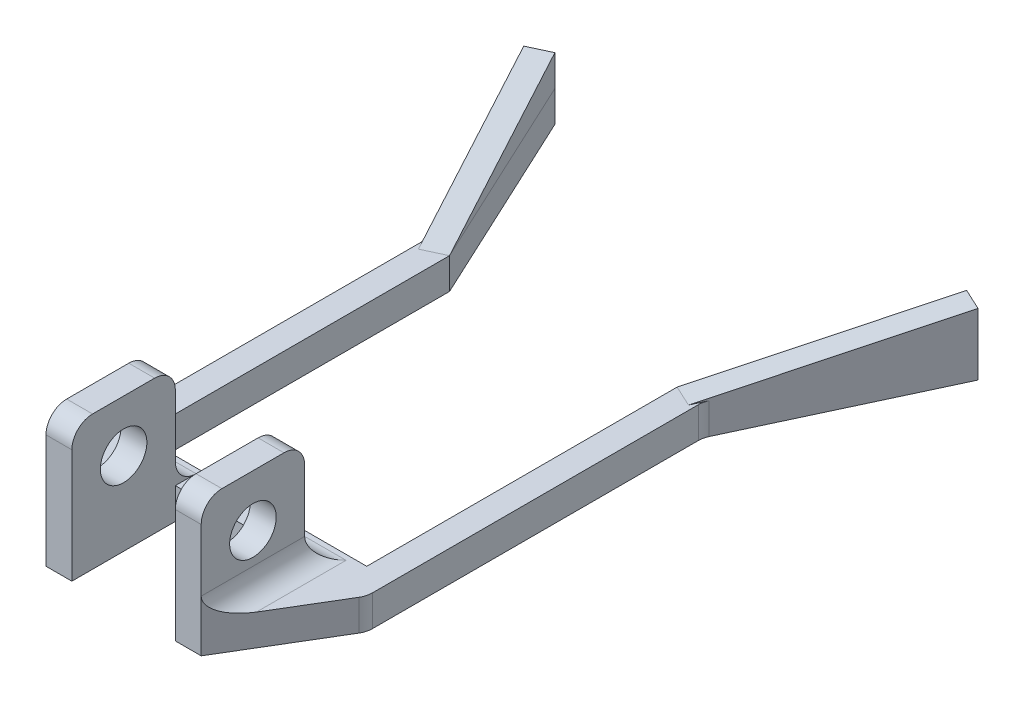
SolidWorks part; units mm, degrees
material "PET"
ref_plane "Front Plane" through (0, 0, 0) normal (0, 0, 1) x (1, 0, 0)
ref_plane "Top Plane" through (0, 0, 0) normal (0, 1, 0) x (1, 0, 0)
ref_plane "Right Plane" through (0, 0, 0) normal (1, 0, 0) x (0, 0, -1)
sketch "Sketch1" plane through (0, 0, 0) normal (0, 1, 0) x (1, 0, 0)
  line L0 (0, -55) -> (0, 55) construction
  line L12 (11, 0) -> (11, 30)
  line L15 (-11, 0) -> (-11, 30)
  line L16 (-11, 0) -> (11, 0)
  line L17 (-13.5, 30) -> (-13.5, -2.5)
  line L18 (13.5, -2.5) -> (13.5, 30)
  line L19 (-11, 30) -> (-19.8989, 49.0837)
  line L20 (-19.8989, 49.0837) -> (-21.9524, 48.1262)
  line L21 (-21.9524, 48.1262) -> (-13.5, 30)
  line L22 (19.8989, 49.0837) -> (21.9524, 48.1262)
  line L23 (21.9524, 48.1262) -> (13.5, 30)
  line L24 (11, 30) -> (19.8989, 49.0837)
  line L25 (5, -2.5) -> (5, -12.5)
  line L26 (5, -12.5) -> (7.5, -12.5)
  line L29 (-5, -2.5) -> (-5, -12.5)
  line L30 (-5, -12.5) -> (-7.5, -12.5)
  line L32 (-5, -2.5) -> (5, -2.5)
  line L33 (7.5, -12.5) -> (13.5, -2.5)
  line L34 (-13.5, -2.5) -> (-7.5, -12.5)
  point P0 (0, 0)
  dimension "D1" = 22
  dimension "D3" = 2.5
  dimension "D4" = 20
  dimension "D5" = 155
  dimension "D6" = 30
  dimension "D7" = 2.5
extrude "Boss-Extrude1" add sketch "Sketch1" along normal blind 3
sketch "Sketch2" plane through (2.4553, 0, -1.1449) normal (0.9063, 0, -0.4226) x (-0.4226, 0, -0.9063)
  line L0 (31.838, 3) -> (52.8946, 6)
  line L1 (52.8946, 6) -> (52.8946, 3)
  line L2 (31.838, 3) -> (52.8946, 3) construction
  line L3 (31.838, 3) -> (52.8946, 3)
  dimension "D1" = 3
extrude "Boss-Extrude2" add sketch "Sketch2" against normal up to surface (2.2658 mm away) separate body up to face at (-17.7262, 1.5, -39.0631)
mirror "Mirror4" about plane through (0, 0, 0) normal (1, 0, 0) of "Boss-Extrude2"
sketch "Sketch3" plane through (0, 3, 0) normal (0, 1, 0) x (1, 0, 0)
  line L0 (-5, -2.5) -> (5, -2.5) construction
  line L23 (5, -12.5) -> (7.5, -12.5) construction
  line L24 (7.5, -12.5) -> (5, -12.5)
  line L25 (7.5, -12.5) -> (7.5, -2.5)
  line L26 (7.5, -2.5) -> (5, -2.5)
  line L27 (5, -12.5) -> (5, -2.5)
  line L28 (5, -2.5) -> (5, -12.5) construction
  line L29 (0, -7.15) -> (0, 7.15) construction
  line L30 (-7.5, -2.5) -> (-5, -2.5)
  line L31 (-5, -12.5) -> (-5, -2.5)
  line L32 (-7.5, -12.5) -> (-5, -12.5)
  line L33 (-7.5, -12.5) -> (-7.5, -2.5)
  line L34 (-13.5, -2.5) -> (-7.5, -12.5) construction
  line L35 (-7.5, -12.5) -> (-5, -12.5) construction
extrude "Boss-Extrude3" add sketch "Sketch3" along normal blind 10
sketch "Sketch4" plane through (7.5, 0, 0) normal (1, 0, 0) x (0, 0, -1)
  line L0 (-12.5, 13) -> (-2.5, 13) construction
  line L1 (-2.5, 13) -> (-2.5, 3) construction
  circle A0 centre (-7.5, 8) radius 2.25
  point P5 (-7.5, 13)
  point P8 (-2.5, 8)
  dimension "D1" = 4.5
extrude "Cut-Extrude1" cut sketch "Sketch4" against normal through all
fillet "Fillet1" radius 2 12 edges at (-7.5, 3, 7.5) (7.5, 3, 7.5) (6.25, 3, 2.5) (-6.25, 3, 2.5) (13.5, 1.5, -30) (13.5, 1.5, 2.5) (-13.5, 1.5, -30) (-13.5, 1.5, 2.5) (6.25, 13, 12.5) (6.25, 13, 2.5) (-6.25, 13, 2.5) (-6.25, 13, 12.5)
